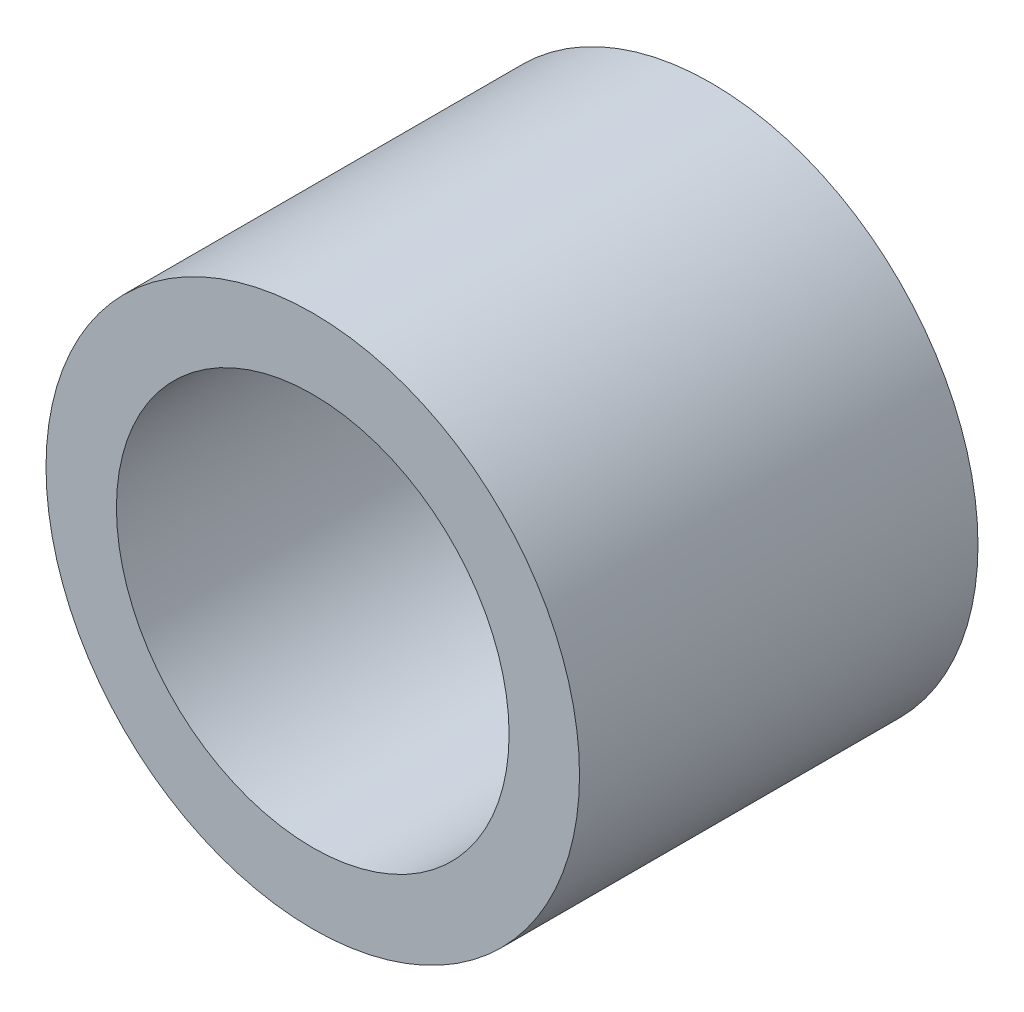
SolidWorks part; units mm, degrees
ref_plane "Front Plane" through (0, 0, 0) normal (0, 0, 1) x (1, 0, 0)
ref_plane "Top Plane" through (0, 0, 0) normal (0, 1, 0) x (1, 0, 0)
ref_plane "Right Plane" through (0, 0, 0) normal (1, 0, 0) x (0, 0, -1)
sketch "Sketch1" plane through (0, 0, 0) normal (0, 0, 1) x (1, 0, 0)
  circle A0 centre (0, 0) radius 4.0894
  circle A1 centre (0, 0) radius 5.5562
  dimension "D1" = 11.1125
  dimension "D2" = 8.1788
extrude "Boss-Extrude1" add sketch "Sketch1" along normal up to surface (8.3 mm away)
